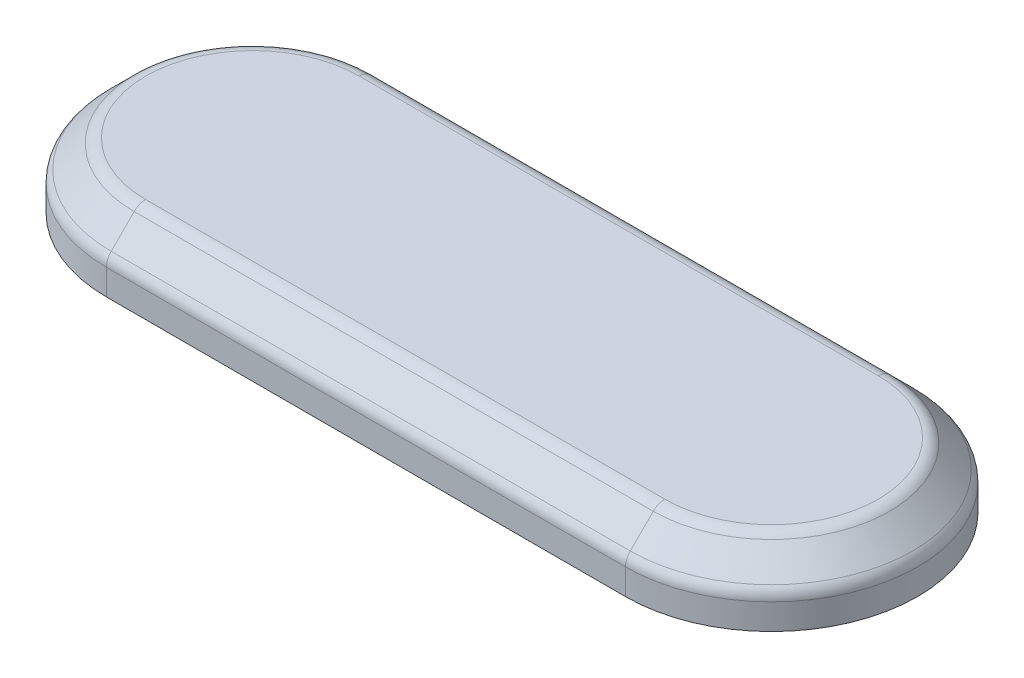
SolidWorks part; units mm, degrees
material "ABS"
ref_plane "Front Plane" through (0, 0, 0) normal (0, 0, 1) x (1, 0, 0)
ref_plane "Top Plane" through (0, 0, 0) normal (0, 1, 0) x (1, 0, 0)
ref_plane "Right Plane" through (0, 0, 0) normal (1, 0, 0) x (0, 0, -1)
sketch "Sketch1" plane through (0, 0, 0) normal (0, 1, 0) x (1, 0, 0)
  line L0 (8, 0) -> (-8, 0) construction
  line L1 (8, -4.5) -> (-8, -4.5)
  line L2 (-2.5, 4.5) -> (-2.5, -4.5) construction
  line L3 (8, 4.5) -> (-8, 4.5)
  line L4 (2.5, 4.5) -> (2.5, -4.5) construction
  line L5 (-2.5, 0) -> (2.5, 0) construction
  line L6 (-4.5, 0) -> (-4.5, -4.5) construction
  circle A0 centre (-8, 0) radius 1.65 construction
  circle A1 centre (8, 0) radius 1.65 construction
  arc A2 (-8, 4.5) -> (-8, -4.5) centre (-8, 0) ccw
  arc A3 (8, -4.5) -> (8, 4.5) centre (8, 0) ccw
  circle A4 centre (-8, 0) radius 3.5 construction
  point P0 (0, 0)
  point P9 (0, 0)
  point P17 (0, 0)
  dimension "D2" = 3.3
  dimension "D5" = 7
  dimension "D4" = 1
  dimension "D6" = 16
  dimension "D1" = 2
  dimension "D3" = 5
extrude "Boss-Extrude1" add sketch "Sketch1" along normal blind 2
sketch "Sketch2" plane through (0, 2, 0) normal (0, 1, 0) x (1, 0, 0)
  line L0 (8, 0) -> (-8, 0)
  arc A1 (-8, 4.5) -> (-8, -4.5) centre (-8, 0) ccw construction
  point P4 (0, 0)
hole_wizard "Tap Drill for M3x0.5 Tap1" positions "Sketch4" profile "Sketch3" hole size "M3x0.5" standard "ANSI Metric"
sketch "Sketch4" plane through (0, 0, 0) normal (0, 1, 0) x (1, 0, 0)
  point P0 (-8, 0)
  point P3 (8, 0)
sketch "Sketch3" plane through (-8, 0, 0) normal (1, 0, 0) x (0, 0, -1)
  line L0 (0, 0) -> (0, 1.7511)
  line L1 (0, 1.7511) -> (1.25, 1)
  line L2 (1.25, 1) -> (1.25, 0)
  line L5 (1.25, 0) -> (0, 0)
  line L10 (0, 1.7511) -> (-1.25, 1) construction
  line L11 (0, -6.35) -> (0, 107.95) construction
  dimension "Hole Dia." = 2.5
  dimension "Hole Depth" = 1
  dimension "Drill Angle" = 118
chamfer "Chamfer3" distance 1 angle 45 4 edges at (12.5, 2, 0) (0, 2, -4.5) (-12.5, 2, 0) (0, 2, 4.5)
fillet "Fillet1" radius 0.5 8 edges at (0, 2, -3.5) (0, 2, 3.5) (11.5, 2, 0) (0, 1, 4.5) (12.5, 1, 0) (0, 1, -4.5) (-11.5, 2, 0) (-12.5, 1, 0)
